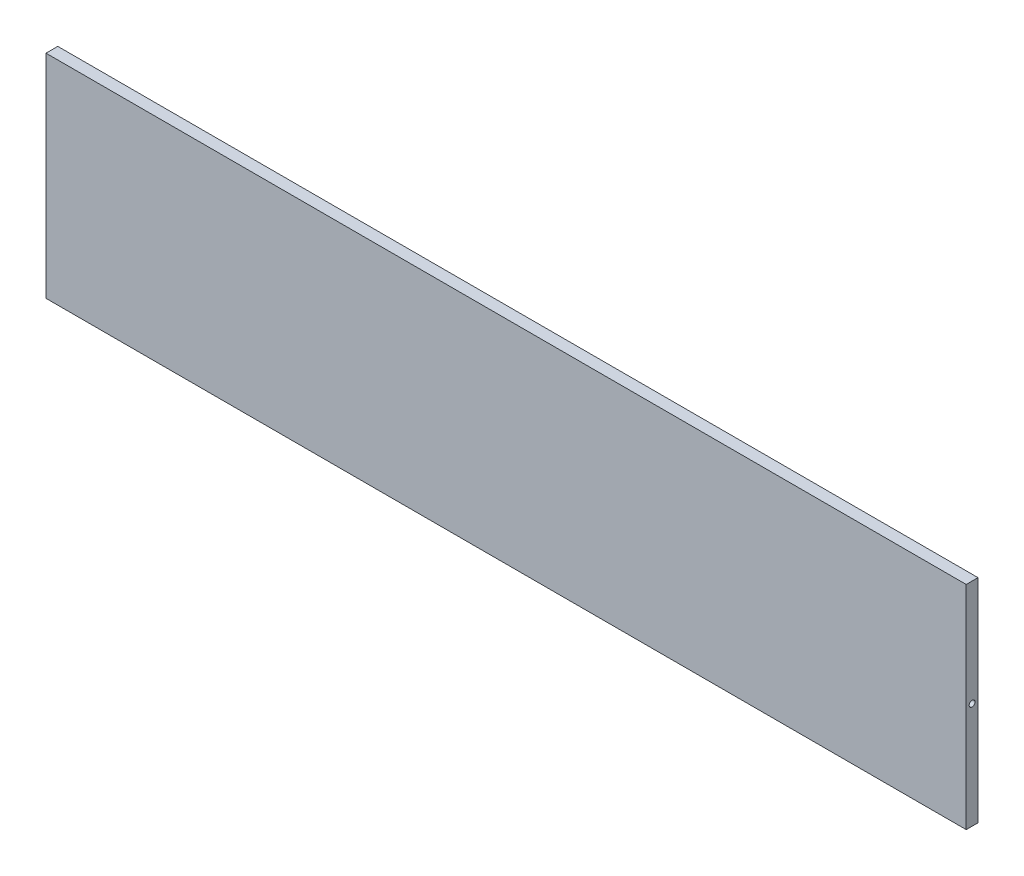
SolidWorks part; units mm, degrees
ref_plane "Front Plane" through (0, 0, 0) normal (0, 0, 1) x (1, 0, 0)
ref_plane "Top Plane" through (0, 0, 0) normal (0, 1, 0) x (1, 0, 0)
ref_plane "Right Plane" through (0, 0, 0) normal (1, 0, 0) x (0, 0, -1)
sketch "Sketch1" plane through (0, 0, 0) normal (0, 0, 1) x (1, 0, 0)
  line L1 (0, 0) -> (390, 0)
  line L2 (0, 0) -> (0, 90)
  line L3 (0, 90) -> (390, 90)
  line L4 (390, 0) -> (390, 90)
  dimension "D1" = 90
  dimension "D2" = 390
extrude "Boss-Extrude1" add sketch "Sketch1" along normal blind 5
sketch "Sketch2" plane through (0, 0, 0) normal (-1, 0, 0) x (0, 0, 1)
  line L0 (0, 90) -> (0, 0) construction
  line L2 (5, 90) -> (0, 90) construction
  circle A0 centre (2.5, 45) radius 1.25
  dimension "D1" = 2.5
  dimension "D2" = 45
extrude "Cut-Extrude1" cut sketch "Sketch2" against normal blind 15
sketch "Sketch3" plane through (0, 0, 0) normal (0, -1, 0) x (-1, 0, 0)
  line L0 (-390, -5) -> (-390, 0) construction
  line L1 (0, -5) -> (-390, -5) construction
  line L2 (0, -5) -> (0, 0) construction
  circle A0 centre (-35, -2.5) radius 1.25
  circle A1 centre (-355, -2.5) radius 1.25
  dimension "D1" = 35
  dimension "D2" = 2.5
  dimension "D3" = 35
  dimension "D4" = 2.5
extrude "Cut-Extrude2" cut sketch "Sketch3" against normal blind 15
sketch "Sketch4" plane through (390, 0, 0) normal (1, 0, 0) x (0, 0, -1)
  line L0 (-5, 0) -> (-5, 90) construction
  line L1 (-5, 90) -> (0, 90) construction
  circle A0 centre (-2.5, 45) radius 1.25
  dimension "D1" = 2.5
  dimension "D2" = 45
extrude "Cut-Extrude3" cut sketch "Sketch4" against normal blind 15
